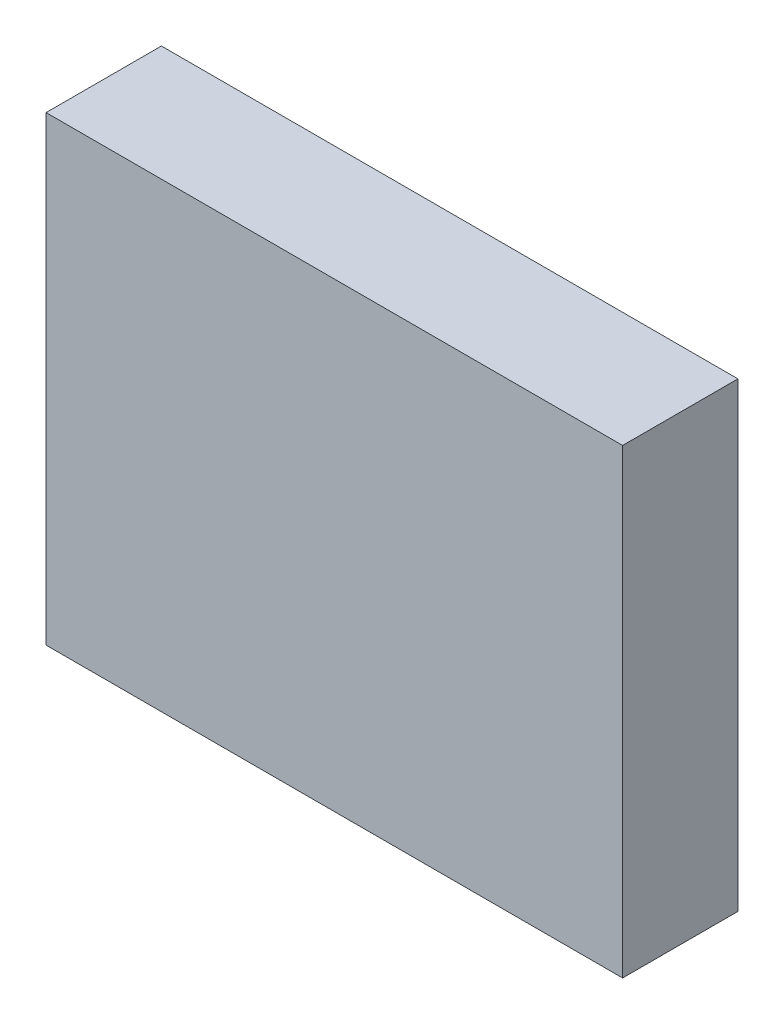
SolidWorks part; units mm, degrees
ref_plane "Front Plane" through (0, 0, 0) normal (0, 0, 1) x (1, 0, 0)
ref_plane "Top Plane" through (0, 0, 0) normal (0, 1, 0) x (1, 0, 0)
ref_plane "Right Plane" through (0, 0, 0) normal (1, 0, 0) x (0, 0, -1)
sketch "Sketch1" plane through (0, 0, 0) normal (0, 0, 1) x (1, 0, 0)
  line L1 (0, 0) -> (500, 0)
  line L2 (0, 0) -> (0, -400)
  line L3 (0, -400) -> (500, -400)
  line L4 (500, 0) -> (500, -400)
  dimension "D1" = 500
  dimension "D2" = 400
extrude "Boss-Extrude1" add sketch "Sketch1" along normal blind 100
